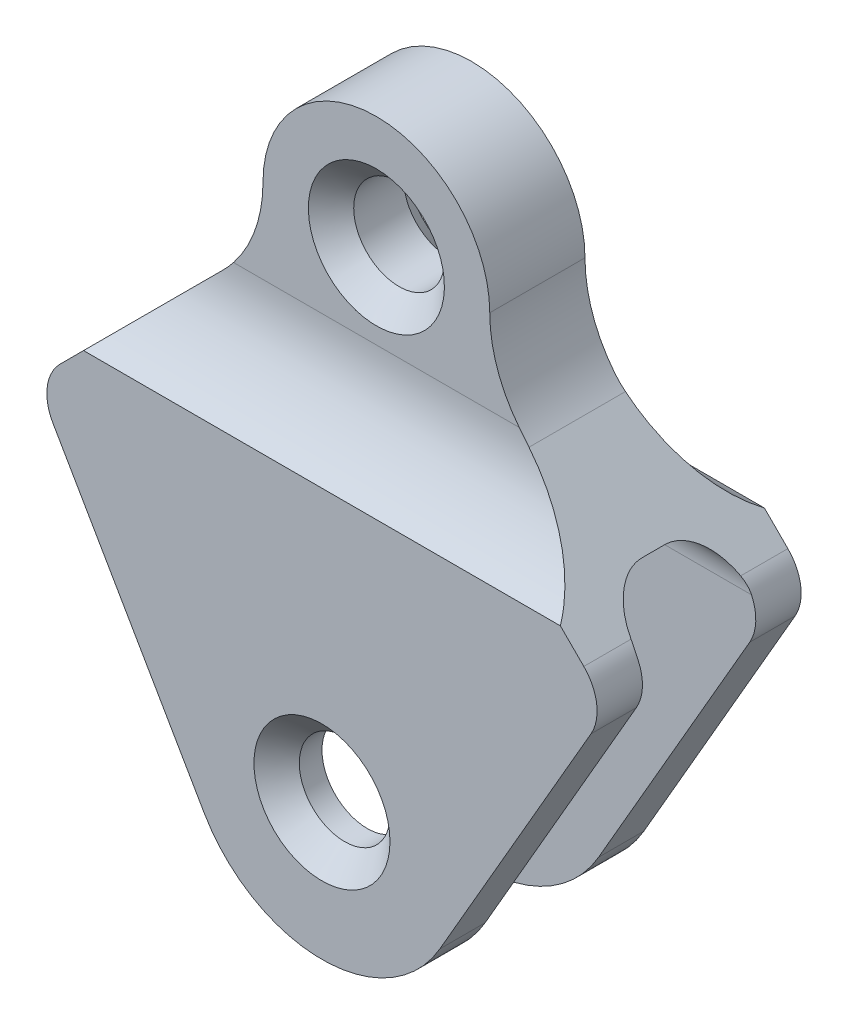
SolidWorks part; units mm, degrees
ref_plane "Front Plane" through (0, 0, 0) normal (0, 0, 1) x (1, 0, 0)
ref_plane "Top Plane" through (0, 0, 0) normal (0, 1, 0) x (1, 0, 0)
ref_plane "Right Plane" through (0, 0, 0) normal (1, 0, 0) x (0, 0, -1)
sketch "Sketch1" plane through (0, 0, 0) normal (0, 0, 1) x (1, 0, 0)
  line L0 (0, 0) -> (0, 100) construction
  line L1 (-25.9808, -15) -> (-59.3297, 42.762)
  line L2 (-57.7405, 54.8331) -> (-33.7868, 78.7868)
  line L3 (25.9808, -15) -> (59.3297, 42.762)
  line L4 (57.7405, 54.8331) -> (33.7868, 78.7868)
  circle A0 centre (0, 0) radius 10
  circle A1 centre (0, 0) radius 30
  arc A2 (-59.3297, 42.762) -> (-57.7405, 54.8331) centre (-50.6694, 47.762) cw
  circle A3 centre (0, 100) radius 10
  circle A4 centre (0, 100) radius 25
  arc A5 (-25, 100) -> (-33.7868, 78.7868) centre (-55, 100) cw
  arc A6 (59.3297, 42.762) -> (57.7405, 54.8331) centre (50.6694, 47.762) ccw
  arc A7 (25, 100) -> (33.7868, 78.7868) centre (55, 100) ccw
  point P14 (0, 0)
  dimension "D1" = 20
  dimension "D2" = 20
  dimension "D4" = 10
  dimension "D5" = 20
  dimension "D7" = 30
  dimension "D9" = 50
  dimension "D3" = 30
  dimension "D6" = 100
  dimension "D8" = 45
extrude "Boss-Extrude1" add sketch "Sketch1" along normal mid plane 45
sketch "Sketch2" plane through (0, 0, 0) normal (1, 0, 0) x (0, 0, -1)
  line L0 (0, 0) -> (0, -30) construction
  line L1 (-22.5, -30) -> (22.5, -30) construction
  line L3 (-2.5, 62) -> (2.5, 62)
  line L4 (-12.5, 52) -> (-12.5, -30)
  line L5 (-12.5, -30) -> (12.5, -30)
  line L6 (12.5, 52) -> (12.5, -30)
  arc A0 (12.5, 52) -> (2.5, 62) centre (2.5, 52) ccw
  arc A1 (-12.5, 52) -> (-2.5, 62) centre (-2.5, 52) cw
  point P11 (12.5, 62)
  point P14 (-12.5, 62)
  dimension "D3" = 10
  dimension "D1" = 25
  dimension "D2" = 92
extrude "Cut-Extrude1" cut sketch "Sketch2" against normal through all both and the other way through all
sketch "Sketch3" plane through (0, 0, 0) normal (1, 0, 0) x (0, 0, -1)
  line L0 (-10.5, 125) -> (-10.5, 81.3542)
  line L3 (22.5, 125) -> (-22.5, 125) construction
  line L5 (-22.5, 54.8331) -> (-22.5, 78.7868) construction
  line L6 (-22.5, 125) -> (-22.5, 100) construction
  line L7 (-10.5, 125) -> (-22.5, 125)
  line L8 (-22.5, 125) -> (-22.5, 60)
  arc A0 (-10.5, 81.3542) -> (-22.5, 60) centre (-35.5, 81.3542) cw
  dimension "D2" = 25
  dimension "D3" = 65
  dimension "D1" = 12
extrude "Cut-Extrude2" cut sketch "Sketch3" against normal through all both and the other way through all
mirror "Mirror1" about plane through (0, 0, 0) normal (0, 0, 1) of "Cut-Extrude2"
chamfer "Chamfer1" distance 5 angle 45 4 edges at (10, 0, 22.5) (10, 0, -22.5) (0, 110, -10.5) (0, 110, 10.5)
